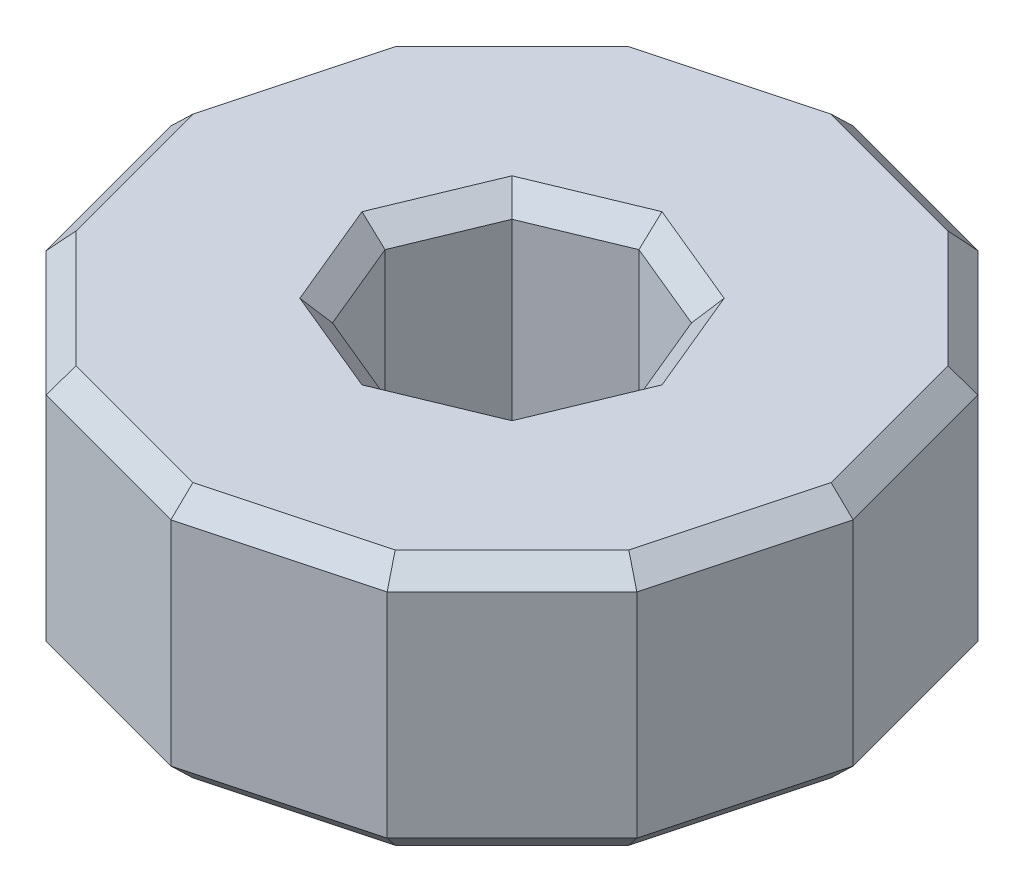
SolidWorks part; units mm, degrees
ref_plane "Front Plane" through (0, 0, 0) normal (0, 0, 1) x (1, 0, 0)
ref_plane "Top Plane" through (0, 0, 0) normal (0, 1, 0) x (1, 0, 0)
ref_plane "Right Plane" through (0, 0, 0) normal (1, 0, 0) x (0, 0, -1)
sketch "Sketch1" plane through (0, 0, 0) normal (0, 1, 0) x (1, 0, 0)
  line L1 (8, 0) -> (6.9282, 4)
  line L2 (6.9282, 4) -> (4, 6.9282)
  line L3 (4, 6.9282) -> (0, 8)
  line L4 (0, 8) -> (-4, 6.9282)
  line L5 (-4, 6.9282) -> (-6.9282, 4)
  line L6 (-6.9282, 4) -> (-8, 0)
  line L7 (-8, 0) -> (-6.9282, -4)
  line L8 (-6.9282, -4) -> (-4, -6.9282)
  line L9 (-4, -6.9282) -> (0, -8)
  line L10 (0, -8) -> (4, -6.9282)
  line L11 (4, -6.9282) -> (6.9282, -4)
  line L12 (6.9282, -4) -> (8, 0)
  line L13 (2.9766, 0) -> (2.1048, 2.1048)
  line L14 (2.1048, 2.1048) -> (0, 2.9766)
  line L15 (0, 2.9766) -> (-2.1048, 2.1048)
  line L16 (-2.1048, 2.1048) -> (-2.9766, 0)
  line L17 (-2.9766, 0) -> (-2.1048, -2.1048)
  line L18 (-2.1048, -2.1048) -> (0, -2.9766)
  line L19 (0, -2.9766) -> (2.1048, -2.1048)
  line L20 (2.1048, -2.1048) -> (2.9766, 0)
  circle A4 centre (0, 0) radius 7.7274 construction
  circle A5 centre (0, 0) radius 2.75 construction
  dimension "D1" = 16
  dimension "D2" = 5.5
extrude "Boss-Extrude1" add sketch "Sketch1" along normal blind 6
chamfer "Chamfer1" distance 0.5 angle 45 40 edges at (1.0524, 0, 2.5407) (-1.0524, 0, 2.5407) (-2.5407, 0, 1.0524) (-2.5407, 0, -1.0524) (-1.0524, 0, -2.5407) (1.0524, 0, -2.5407) (2.5407, 0, -1.0524) (2.5407, 0, 1.0524) (7.4641, 0, -2) (5.4641, 0, -5.4641) (2, 0, -7.4641) (-2, 0, -7.4641) (-5.4641, 0, -5.4641) (-7.4641, 0, -2) (-7.4641, 0, 2) (-5.4641, 0, 5.4641) (-2, 0, 7.4641) (2, 0, 7.4641) (5.4641, 0, 5.4641) (7.4641, 0, 2) (1.0524, 6, -2.5407) (-1.0524, 6, -2.5407) (-2.5407, 6, -1.0524) (-2.5407, 6, 1.0524) (-1.0524, 6, 2.5407) (1.0524, 6, 2.5407) (2.5407, 6, 1.0524) (2.5407, 6, -1.0524) (5.4641, 6, 5.4641) (2, 6, 7.4641) (-2, 6, 7.4641) (-5.4641, 6, 5.4641) (-7.4641, 6, 2) (-7.4641, 6, -2) (-5.4641, 6, -5.4641) (-2, 6, -7.4641) (2, 6, -7.4641) (5.4641, 6, -5.4641) (7.4641, 6, -2) (7.4641, 6, 2)
